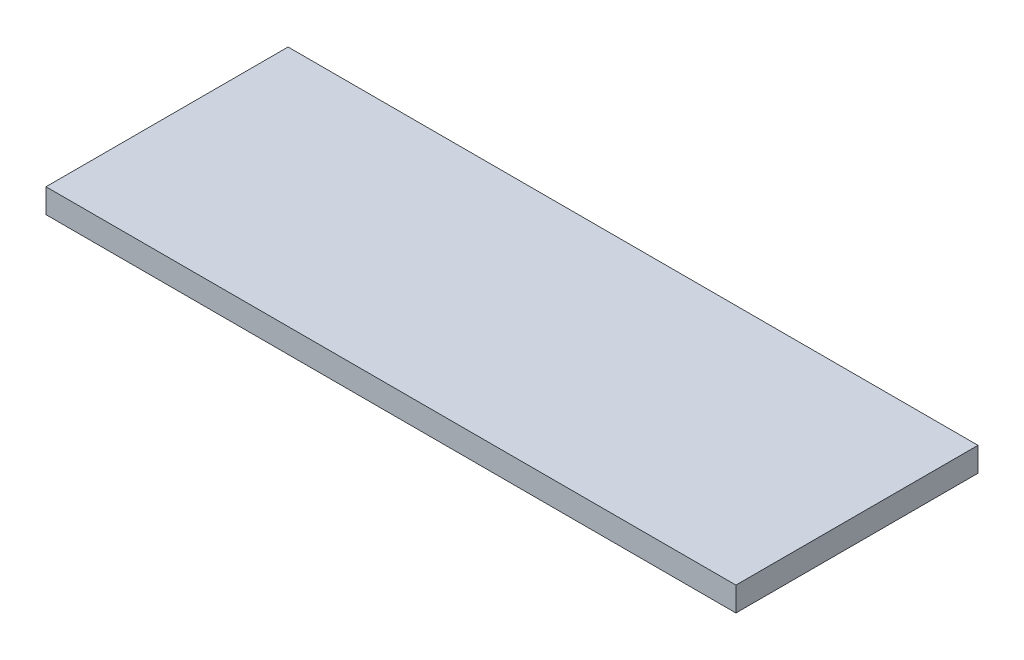
SolidWorks part; units mm, degrees
ref_plane "Front Plane" through (0, 0, 0) normal (0, 0, 1) x (1, 0, 0)
ref_plane "Top Plane" through (0, 0, 0) normal (0, 1, 0) x (1, 0, 0)
ref_plane "Right Plane" through (0, 0, 0) normal (1, 0, 0) x (0, 0, -1)
sketch "Sketch1" plane through (0, 0, 0) normal (0, 0, 1) x (1, 0, 0)
  line L1 (-44.3111, 20.1056) -> (-15.8111, 20.1056)
  line L2 (-44.3111, 20.1056) -> (-44.3111, 10.1056)
  line L3 (-44.3111, 10.1056) -> (-15.8111, 10.1056)
  line L4 (-15.8111, 20.1056) -> (-15.8111, 10.1056)
  line L5 (-30.0611, 10.1056) -> (-30.0611, 20.1056) construction
  line L6 (-44.3111, 15.1056) -> (-15.8111, 15.1056) construction
  point P104 (-30.0611, 15.1056)
  dimension "D1" = 10
  dimension "D2" = 28.5
extrude "Boss-Extrude1" add sketch "Sketch1" along normal blind 1
move or copy body "Body-Move/Copy1" bodies to move or copy 102 copy no rotation origin (0, 15.1056, 0.25) rotation axis (1, 0, 0) rotation angle 90
